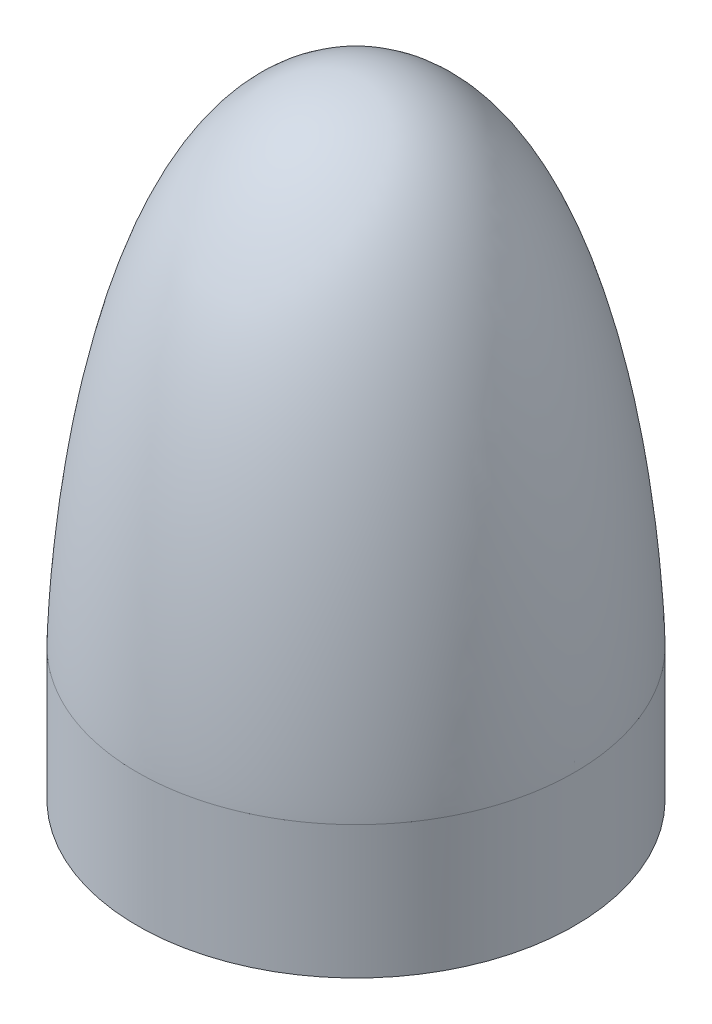
SolidWorks part; units mm, degrees
ref_plane "Front Plane" through (0, 0, 0) normal (0, 0, 1) x (1, 0, 0)
ref_plane "Top Plane" through (0, 0, 0) normal (0, 1, 0) x (1, 0, 0)
ref_plane "Right Plane" through (0, 0, 0) normal (1, 0, 0) x (0, 0, -1)
sketch "Sketch1" plane through (0, 0, 0) normal (0, 0, 1) x (1, 0, 0)
  line L0 (7, 4.2563) -> (7, 0)
  line L1 (0, 0) -> (7, 0)
  line L2 (0, 0) -> (0, 20)
  spline S0 degree 3 poles (0, 20) (6.7488, 19.9833) (7.0051, 4.2567) (7, 4.2563) knots 0 0 0 0 0.166417 0.166417 0.166417 0.166417
  dimension "D1" = 7
  dimension "D2" = 20
revolve "Revolve1" add sketch "Sketch1" angle 360 about L2
scale "Scale2" bodies to scale 101 scale about centroid uniform scaling yes scale factor 2
